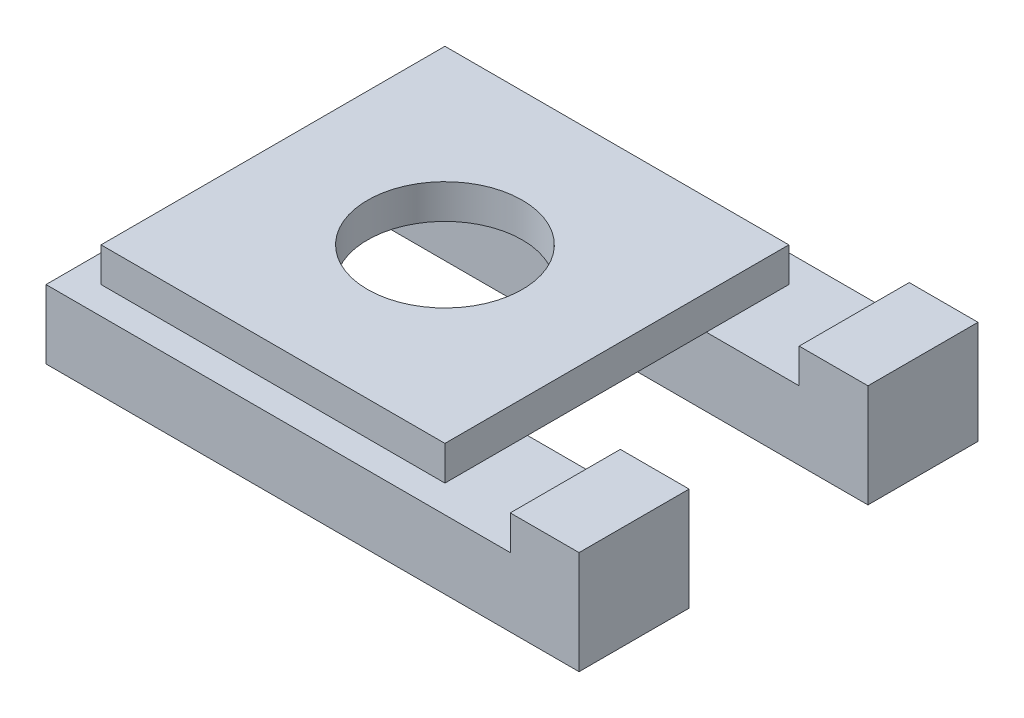
SolidWorks part; units mm, degrees
ref_plane "Front Plane" through (0, 0, 0) normal (0, 0, 1) x (1, 0, 0)
ref_plane "Top Plane" through (0, 0, 0) normal (0, 1, 0) x (1, 0, 0)
ref_plane "Right Plane" through (0, 0, 0) normal (1, 0, 0) x (0, 0, -1)
sketch "Sketch1" plane through (0, 0, 0) normal (0, 1, 0) x (1, 0, 0)
  line L1 (50, -50) -> (-50, -50)
  line L2 (50, -50) -> (50, 50)
  line L3 (50, 50) -> (-50, 50)
  line L4 (-50, -50) -> (-50, 50)
  line L5 (50, -50) -> (-50, 50) construction
  line L6 (50, 50) -> (-50, -50) construction
  circle A0 centre (0, 0) radius 22.5
  point P0 (0, 0)
  dimension "D3" = 45
  dimension "D1" = 100
  dimension "D2" = 100
extrude "Boss-Extrude1" add sketch "Sketch1" along normal blind 10
sketch "Sketch2" plane through (0, 0, 50) normal (0, 0, 1) x (1, 0, 0)
  line L0 (-58, 0) -> (-58, -20)
  line L1 (-58, -20) -> (97, -20)
  line L2 (97, -20) -> (97, 10)
  line L3 (97, 10) -> (77, 10)
  line L4 (77, 10) -> (77, 0)
  line L5 (77, 0) -> (-58, 0)
  line L6 (-50, 0) -> (50, 0) construction
  line L7 (-50, 10) -> (-50, 0) construction
  point P10 (-58, 0)
  point P11 (54.7908, 0)
  point P12 (77, 10)
  dimension "D1" = 8
  dimension "D2" = 10
  dimension "D3" = 20
  dimension "D4" = 155
  dimension "D5" = 30
extrude "Boss-Extrude2" add sketch "Sketch2" against normal blind 32 from offset 8
mirror "Mirror1" about plane through (0, 0, 0) normal (0, 0, 1) of "Boss-Extrude2"
